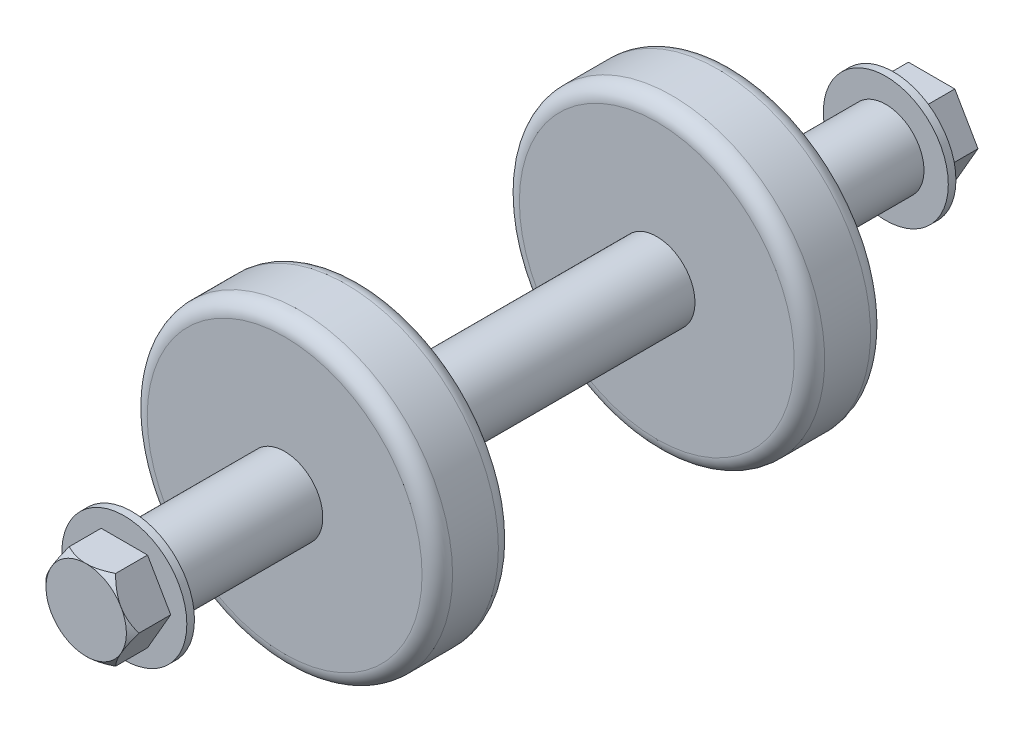
SolidWorks part; units mm, degrees
ref_plane "Front Plane" through (0, 0, 0) normal (0, 0, 1) x (1, 0, 0)
ref_plane "Top Plane" through (0, 0, 0) normal (0, 1, 0) x (1, 0, 0)
ref_plane "Right Plane" through (0, 0, 0) normal (1, 0, 0) x (0, 0, -1)
sketch "Sketch2" plane through (0, 0, 0) normal (0, 0, 1) x (1, 0, 0)
  circle A0 centre (0, 0) radius 25
  dimension "D1" = 50
extrude "Boss-Extrude1" add sketch "Sketch2" along normal mid plane 493.75
ref_plane "Plane1" through (0, 0, 146.875) normal (0, 0, 1) x (1, 0, 0)
sketch "Sketch3" plane through (0, 0, 146.875) normal (0, 0, 1) x (1, 0, 0)
  circle A0 centre (0, 0) radius 100
  dimension "D1" = 200
extrude "Boss-Extrude2" add sketch "Sketch3" against normal blind 50
mirror "Mirror1" about plane through (0, 0, 0) normal (0, 0, 1) of "Boss-Extrude2"
fillet "Fillet1" radius 10 4 edges at (100, 0, -146.875) (100, 0, -96.875) (100, 0, 146.875) (100, 0, 96.875)
sketch "Sketch4" plane through (0, 0, 246.875) normal (0, 0, 1) x (1, 0, 0)
  circle A0 centre (0, 0) radius 40.935
  dimension "D1" = 81.87
extrude "Boss-Extrude3" add sketch "Sketch4" along normal blind 5
sketch "Sketch5" plane through (0, 0, 251.875) normal (0, 0, 1) x (1, 0, 0)
  line L1 (30.3802, 0) -> (15.1901, 26.31)
  line L2 (15.1901, 26.31) -> (-15.1901, 26.31)
  line L3 (-15.1901, 26.31) -> (-30.3802, 0)
  line L4 (-30.3802, 0) -> (-15.1901, -26.31)
  line L5 (-15.1901, -26.31) -> (15.1901, -26.31)
  line L6 (15.1901, -26.31) -> (30.3802, 0)
  circle A0 centre (0, 0) radius 26.31 construction
  dimension "D1" = 52.62
extrude "Boss-Extrude4" add sketch "Sketch5" along normal blind 25
sketch "Sketch6" plane through (0, 0, 276.875) normal (0, 0, 1) x (1, 0, 0)
  circle A0 centre (0, 0) radius 26.31
  circle A1 centre (0, 0) radius 40.935
extrude "Cut-Extrude1" cut sketch "Sketch6" against normal blind 25 draft 45
mirror "Mirror2" about plane through (0, 0, 0) normal (0, 0, 1) of "Boss-Extrude3", "Boss-Extrude4"
